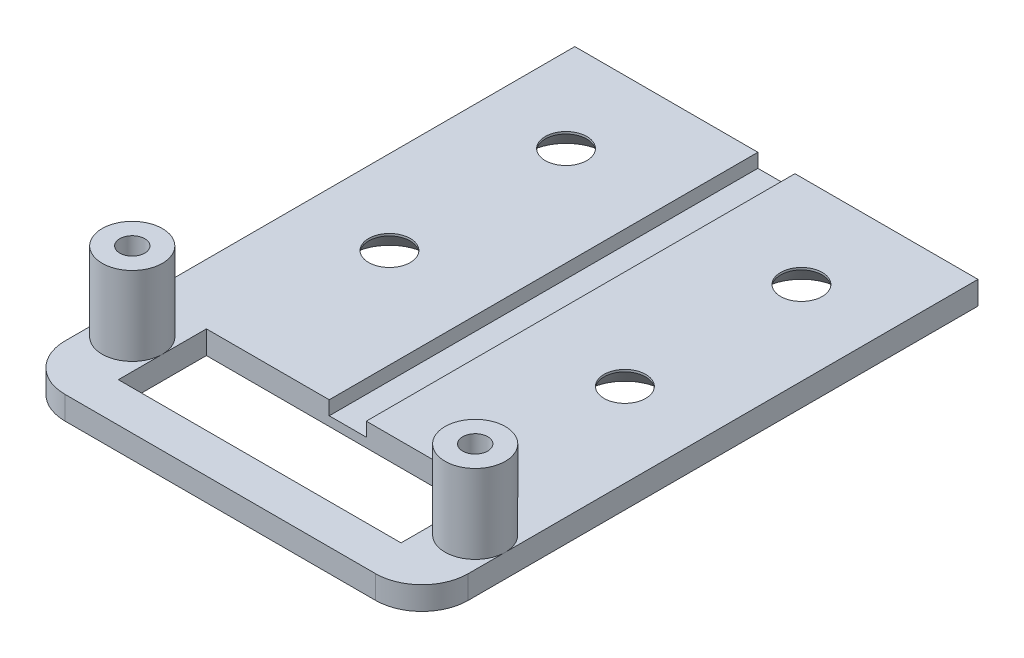
SolidWorks part; units mm, degrees
ref_plane "Front Plane" through (0, 0, 0) normal (0, 0, 1) x (1, 0, 0)
ref_plane "Top Plane" through (0, 0, 0) normal (0, 1, 0) x (1, 0, 0)
ref_plane "Right Plane" through (0, 0, 0) normal (1, 0, 0) x (0, 0, -1)
sketch "Sketch2" plane through (0, 0, 0) normal (0, 1, 0) x (1, 0, 0)
  line L1 (21.75, -30) -> (-21.75, -30)
  line L2 (21.75, -30) -> (21.75, 30)
  line L3 (21.75, 30) -> (-21.75, 30)
  line L4 (-21.75, -30) -> (-21.75, 30)
  line L5 (21.75, -30) -> (-21.75, 30) construction
  line L6 (21.75, 30) -> (-21.75, -30) construction
  point P0 (0, 0)
  dimension "D1" = 43.5
  dimension "D2" = 60
extrude "Boss-Extrude1" add sketch "Sketch2" along normal blind 2.5
sketch "Sketch3" plane through (0, 2.5, 0) normal (0, 1, 0) x (1, 0, 0)
  line L0 (-21.75, -30) -> (21.75, -30) construction
  line L1 (-15.25, -16.25) -> (15.25, -16.25)
  line L2 (-15.25, -16.25) -> (-15.25, -25.75)
  line L3 (-15.25, -25.75) -> (15.25, -25.75)
  line L4 (15.25, -16.25) -> (15.25, -25.75)
  line L5 (-15.25, -16.25) -> (15.25, -25.75) construction
  line L6 (-15.25, -25.75) -> (15.25, -16.25) construction
  point P0 (0, -21)
  dimension "D1" = 30.5
  dimension "D2" = 9.5
  dimension "D3" = 9
extrude "Cut-Extrude1" cut sketch "Sketch3" against normal through all
sketch "Sketch4" plane through (0, 2.5, 0) normal (0, 1, 0) x (1, 0, 0)
  line L0 (-15.25, -16.25) -> (-15.25, -25.75) construction
  line L1 (15.25, -25.75) -> (15.25, -16.25) construction
  line L2 (0, -16.25) -> (0, -25.75) construction
  line L3 (15.25, -16.25) -> (-15.25, -16.25) construction
  line L4 (-15.25, -25.75) -> (15.25, -25.75) construction
  circle A0 centre (-18.5, -21) radius 3.25
  circle A1 centre (18.5, -21) radius 3.25
  point P7 (-15.25, -21)
  point P12 (15.25, -21)
  dimension "D1" = 6.5
  dimension "D2" = 37
extrude "Boss-Extrude2" add sketch "Sketch4" along normal blind 8.5
hole_wizard "Tap Drill for M3x0.5 Tap1" positions "Sketch5" profile "Sketch6" hole size "M3x0.5" standard "ANSI Metric" end condition through all
sketch "Sketch5" plane through (0, 11, 0) normal (0, 1, 0) x (1, 0, 0)
  point P0 (-18.5, -21)
  point P3 (18.5, -21)
sketch "Sketch6" plane through (-18.5, 11, 21) normal (1, 0, 0) x (0, 0, 1)
  line L0 (0, 0) -> (0, 11)
  line L1 (0, 11) -> (1.35, 11)
  line L2 (1.35, 11) -> (1.35, 0)
  line L5 (1.35, 0) -> (0, 0)
  line L11 (0, -6.35) -> (0, 107.95) construction
  dimension "Thru Hole Dia." = 2.7
  dimension "Thru Hole Depth" = 11
fillet "Fillet1" radius 5 2 edges at (-21.75, 1.25, 30) (21.75, 1.25, 30)
sketch "Sketch7" plane through (0, 2.5, 0) normal (0, 1, 0) x (1, 0, 0)
  line L0 (21.75, 30) -> (-21.75, 30) construction
  line L1 (-2, -16.25) -> (2, -16.25)
  line L2 (-2, -16.25) -> (-2, 30)
  line L3 (-2, 30) -> (2, 30)
  line L4 (2, -16.25) -> (2, 30)
  line L5 (-2, -16.25) -> (2, 30) construction
  line L6 (-2, 30) -> (2, -16.25) construction
  line L7 (15.25, -16.25) -> (-15.25, -16.25) construction
  point P0 (0, 6.875)
  point P9 (0, -16.25)
  dimension "D1" = 4
extrude "Cut-Extrude2" cut sketch "Sketch7" against normal blind 1.5
hole_wizard "CSK for #8 Flat Head Machine Screw1" positions "Sketch8" profile "Sketch9" countersink size "#8" standard "ANSI Inch" end condition through all
sketch "Sketch8" plane through (0, 0, 0) normal (0, -1, 0) x (-1, 0, 0)
  line L1 (-12.7, 0.95) -> (12.7, 0.95)
  line L2 (-12.7, 0.95) -> (-12.7, 20)
  line L3 (-12.7, 20) -> (12.7, 20)
  line L4 (12.7, 0.95) -> (12.7, 20)
  line L5 (-12.7, 0.95) -> (12.7, 20) construction
  line L6 (-12.7, 20) -> (12.7, 0.95) construction
  line L7 (-21.75, 30) -> (21.75, 30) construction
  point P0 (-12.7, 0.95)
  point P2 (-12.7, 20)
  point P4 (12.7, 0.95)
  point P6 (12.7, 20)
  point P73 (-13.6333, 22.2116)
  point P74 (0, 0)
  point P76 (0, 10.475)
  point P77 (-13.6333, 5.3163)
  point P78 (13.6333, 5.3163)
  dimension "D1" = 25.4
  dimension "D2" = 19.05
  dimension "D3" = 10
sketch "Sketch9" plane through (12.7, 0, -0.95) normal (1, 0, 0) x (0, 0, -1)
  line L0 (0, 0) -> (0, 11)
  line L1 (0, 11) -> (2.2479, 11)
  line L2 (2.2479, 11) -> (2.2479, 2.2645)
  line L3 (2.2479, 2.2645) -> (4.2164, 0)
  line L5 (4.2164, 0) -> (0, 0)
  line L6 (-2.2479, 2.2645) -> (-4.2164, 0) construction
  line L11 (0, -6.35) -> (0, 107.95) construction
  dimension "Thru Hole Dia." = 4.4958
  dimension "Thru Hole Depth" = 11
  dimension "Near C'Sink Dia." = 8.4328
  dimension "Near C'Sink Angle" = 82
